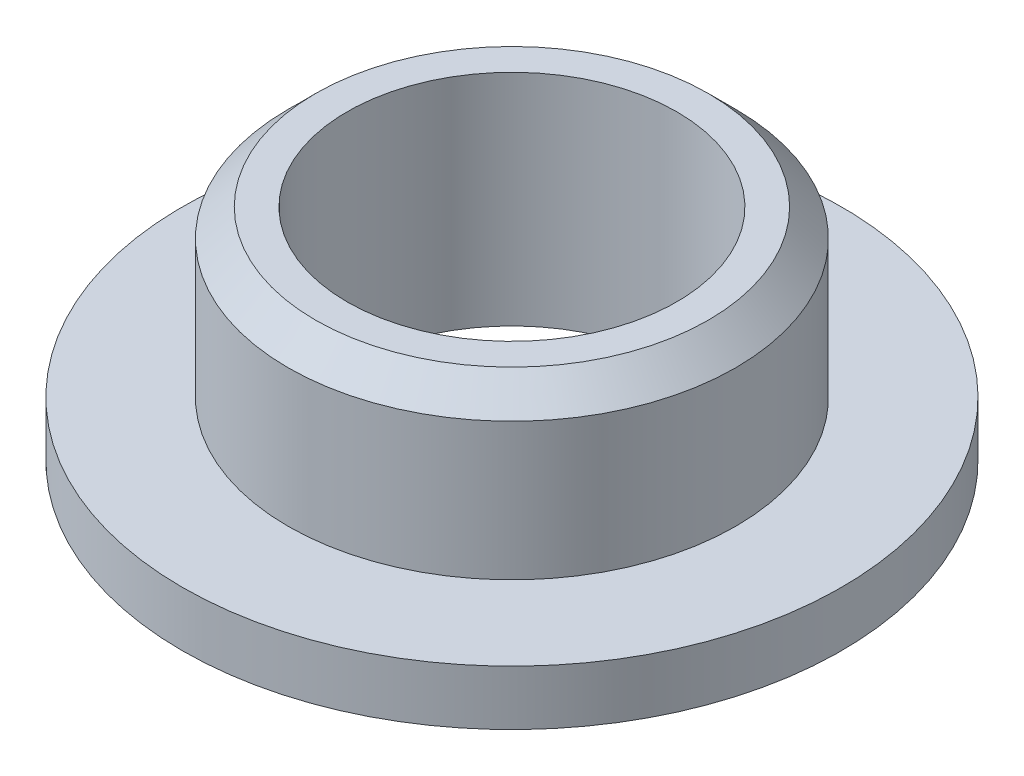
SolidWorks part; units mm, degrees
ref_plane "前视基准面" through (0, 0, 0) normal (0, 0, 1) x (1, 0, 0)
ref_plane "上视基准面" through (0, 0, 0) normal (0, 1, 0) x (1, 0, 0)
ref_plane "右视基准面" through (0, 0, 0) normal (1, 0, 0) x (0, 0, -1)
other "Configuration Table"
sketch "草图1" plane through (0, 0, 0) normal (0, 1, 0) x (1, 0, 0)
  circle A0 centre (-0.1387, 0.1802) radius 6
extrude "凸台-拉伸1" add sketch "草图1" along normal blind 1
sketch "草图2" plane through (0, 1, 0) normal (0, 1, 0) x (1, 0, 0)
  circle A1 centre (-0.1387, 0.1802) radius 4.075
  circle A3 centre (-0.1387, 0.1802) radius 3
  dimension "D1" = 8.15
  dimension "D2" = 6
extrude "凸台-拉伸2" add sketch "草图2" along normal blind 3
sketch "草图3" plane through (0, 1, 0) normal (0, 1, 0) x (1, 0, 0)
  circle A0 centre (-0.1387, 0.1802) radius 3
extrude "切除-拉伸1" cut sketch "草图3" against normal blind 3
chamfer "倒角1" distance 0.5 angle 45 1 edges at (-0.1387, 4, 3.8948)
